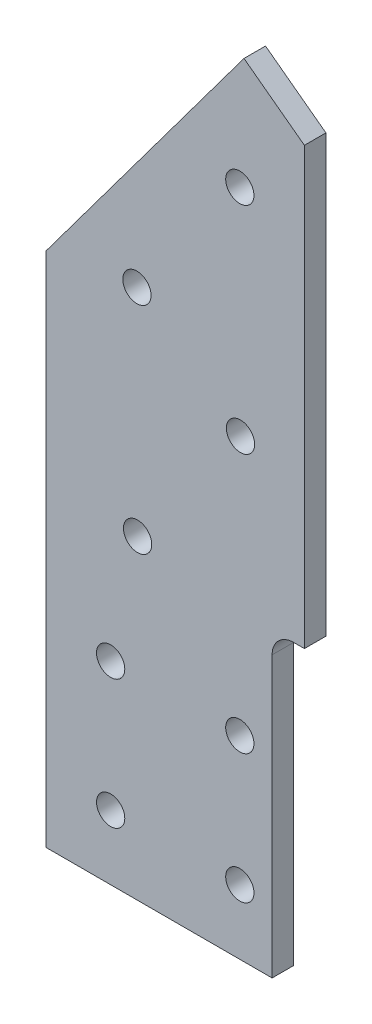
SolidWorks part; units mm, degrees
material "6061-T6 (SS)"
ref_plane "Front" through (0, 0, 0) normal (0, 0, 1) x (1, 0, 0)
ref_plane "Top" through (0, 0, 0) normal (0, 1, 0) x (1, 0, 0)
ref_plane "Right" through (0, 0, 0) normal (1, 0, 0) x (0, 0, -1)
sketch "Sketch2" plane through (0, 0, 0) normal (0, 0, 1) x (1, 0, 0)
  line L0 (0, 0) -> (76.2, 0)
  line L1 (0, 0) -> (0, 152.4)
  line L2 (0, 152.4) -> (58.3782, 230.7489)
  line L3 (76.2, 217.4698) -> (76.2, 0)
  line L4 (58.3782, 230.7489) -> (76.2, 217.4698)
  dimension "D1" = 76.2
  dimension "D2" = 152.4
  dimension "D3" = 53.31
  dimension "D4" = 22.225
extrude "Boss-Extrude1" add sketch "Sketch2" along normal blind 6.35
hole_wizard "21/64 (0.32813) Diameter Hole1" positions "Sketch3" profile "Sketch4" hole size "21/64" standard "ANSI Inch" end condition through all
sketch "Sketch3" plane through (0, 0, 6.35) normal (0, 0, 1) x (1, 0, 0)
  line L0 (76.2, 0) -> (76.2, 217.4698) construction
  line L1 (0, 0) -> (76.2, 0) construction
  point P0 (57.15, 19.05)
  dimension "D1" = 19.05
  dimension "D2" = 19.05
sketch "Sketch4" plane through (57.15, 19.05, 6.35) normal (1, 0, 0) x (0, -1, 0)
  line L0 (0, 0) -> (0, 6.35)
  line L1 (0, 6.35) -> (4.1673, 6.35)
  line L2 (4.1673, 6.35) -> (4.1673, 0)
  line L5 (4.1673, 0) -> (0, 0)
  line L11 (0, -6.35) -> (0, 107.95) construction
  dimension "Thru Hole Dia." = 8.3345
  dimension "Thru Hole Depth" = 6.35
pattern_linear "LPattern1" count 2 spacing 38.1 along (-1, 0, 0) count 2 spacing 38.1 along (0, 1, 0) of "21/64 (0.32813) Diameter Hole1"
hole_wizard "21/64 (0.32813) Diameter Hole2" positions "Sketch5" profile "Sketch6" hole size "21/64" standard "ANSI Inch" end condition through all
sketch "Sketch5" plane through (0, 0, 6.35) normal (0, 0, 1) x (1, 0, 0)
  line L0 (76.2, 0) -> (76.2, 217.4698) construction
  line L1 (58.3782, 230.7489) -> (0, 152.4) construction
  point P0 (57.15, 197.2169)
  dimension "D1" = 19.05
  dimension "D2" = 19.05
sketch "Sketch6" plane through (57.15, 197.2169, 6.35) normal (1, 0, 0) x (0, -1, 0)
  line L0 (0, 0) -> (0, 6.35)
  line L1 (0, 6.35) -> (4.1673, 6.35)
  line L2 (4.1673, 6.35) -> (4.1673, 0)
  line L5 (4.1673, 0) -> (0, 0)
  line L11 (0, -6.35) -> (0, 107.95) construction
  dimension "Thru Hole Dia." = 8.3345
  dimension "Thru Hole Depth" = 6.35
pattern_linear "LPattern2" count 3 spacing 50.8 along (-0.5975, -0.8019, 0) count 2 spacing 38.1 along (0.8019, -0.5975, 0) skipping (0, 1), (2, 0) of "21/64 (0.32813) Diameter Hole2"
sketch "Sketch7" plane through (0, 0, 6.35) normal (0, 0, 1) x (1, 0, 0)
  line L1 (76.2, 0) -> (66.675, 0)
  line L2 (76.2, 0) -> (76.2, 88.9)
  line L3 (76.2, 88.9) -> (66.675, 88.9)
  line L4 (66.675, 0) -> (66.675, 88.9)
  dimension "D1" = 88.9
  dimension "D2" = 9.525
extrude "Cut-Extrude1" cut sketch "Sketch7" against normal through all
fillet "Fillet1" radius 6.35 1 edges at (66.675, 88.9, 3.175)
